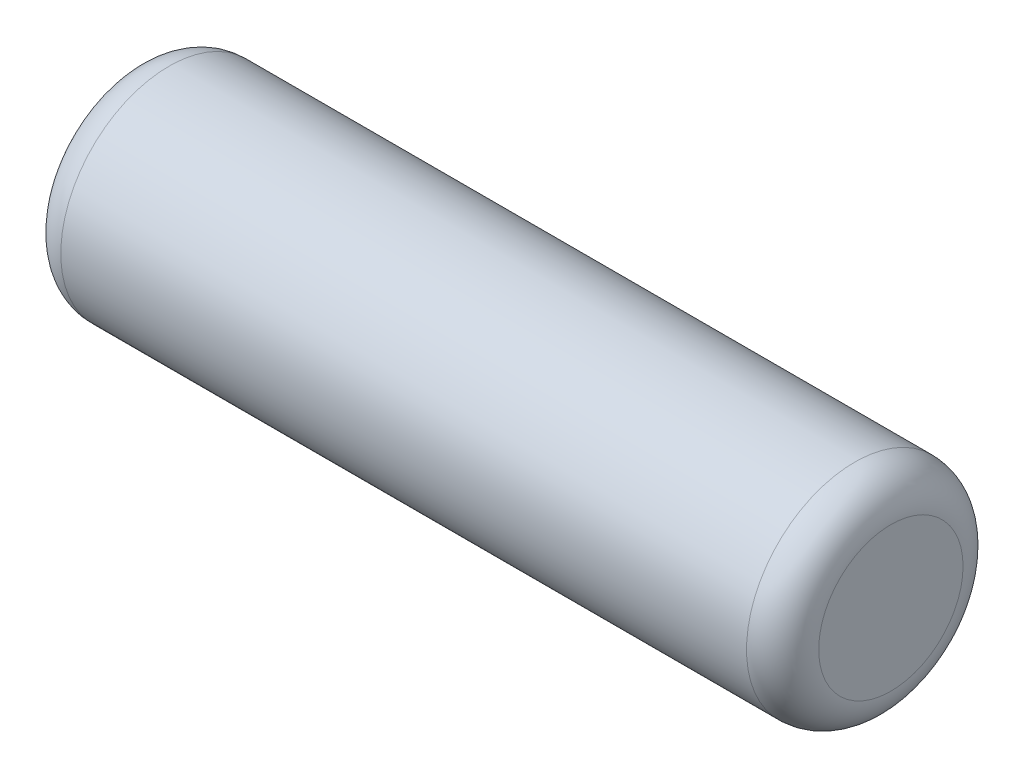
SolidWorks part; units mm, degrees
material "Oak"
ref_plane "Front Plane" through (0, 0, 0) normal (0, 0, 1) x (1, 0, 0)
ref_plane "Top Plane" through (0, 0, 0) normal (0, 1, 0) x (1, 0, 0)
ref_plane "Right Plane" through (0, 0, 0) normal (1, 0, 0) x (0, 0, -1)
sketch "Sketch1" plane through (0, 0, 0) normal (1, 0, 0) x (0, 0, -1)
  circle A0 centre (0, 0) radius 3.81
  dimension "D1" = 7.62
extrude "Boss-Extrude1" add sketch "Sketch1" along normal blind 26.67
fillet "Fillet1" radius 1.27 2 edges at (0, 0, -3.81) (26.67, 0, -3.81)
